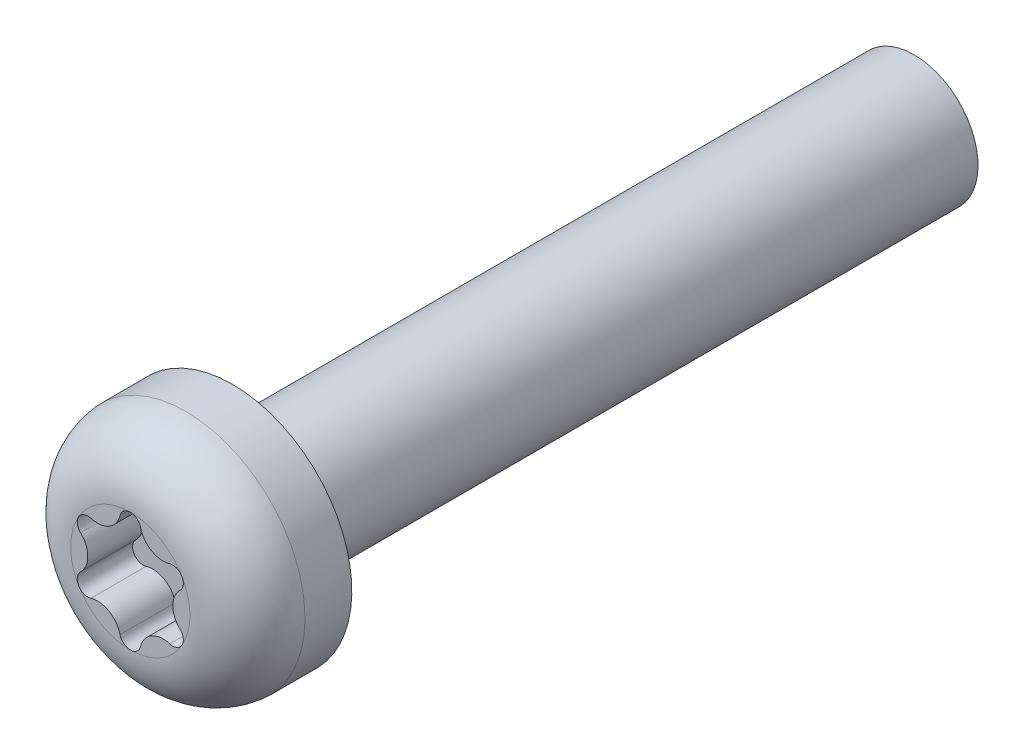
SolidWorks part; units mm, degrees
material "AISI Acier à outil type A2"
ref_plane "Face" through (0, 0, 0) normal (0, 0, 1) x (1, 0, 0)
ref_plane "Dessus" through (0, 0, 0) normal (0, 1, 0) x (1, 0, 0)
ref_plane "Droite" through (0, 0, 0) normal (1, 0, 0) x (0, 0, -1)
sketch "Esquisse1" plane through (0, 0, 0) normal (1, 0, 0) x (0, 0, -1)
  line L0 (-2.4, 0) -> (-2.4, 1.4)
  line L1 (-1.1, 2.8) -> (0, 2.8)
  line L2 (0, 2.8) -> (0, 1.5)
  line L3 (0, 1.5) -> (16, 1.5)
  line L4 (16, 1.5) -> (16, 0)
  line L5 (16, 0) -> (-2.4, 0)
  line L6 (-2.4, 0) -> (-4.3313, 0) construction
  arc A0 (-2.4, 1.4) -> (-1.1, 2.8) centre (-0.9962, 1.4) cw
  dimension "L" = 16
  dimension "K" = 2.4
  dimension "T" = 1.3
  dimension "M" = 3
  dimension "DH" = 5.6
  dimension "A" = 2.8
revolve "Révolution1" add sketch "Esquisse1" angle 360 about L6
sketch "Esquisse2" plane through (0, 0, 2.4) normal (0, 0, 1) x (1, 0, 0)
  line L0 (0, -1.0692) -> (0, 1.0844) construction
  line L1 (0, 0) -> (-0.1844, 0.9269) construction
  line L2 (0, 0) -> (0.1807, 0.9086) construction
  line L3 (0, 0) -> (0.8195, 0.4731) construction
  line L4 (0, 0) -> (0.7063, 0.6194) construction
  line L5 (0, 0) -> (0.3928, 0.6804) construction
  line L7 (0, 1.1524) -> (-0.998, 0.5762) construction
  line L8 (-0.998, 0.5762) -> (-0.998, -0.5762) construction
  line L9 (-0.998, -0.5762) -> (0, -1.1524) construction
  line L10 (0, -1.1524) -> (0.998, -0.5762) construction
  line L11 (0.998, -0.5762) -> (0.998, 0.5762) construction
  line L12 (0.998, 0.5762) -> (0, 1.1524) construction
  circle A0 centre (0, 0) radius 1.4 construction
  circle A1 centre (0, 0) radius 1.4 construction
  arc A2 (-0.2407, 1.2102) -> (0.2407, 1.2102) centre (0, 1.1524) cw
  circle A3 centre (0, 0) radius 0.998 construction
  arc A4 (0.2407, 1.2102) -> (0.9277, 0.8136) centre (0.7724, 1.3379) ccw
  arc A5 (0.9277, 0.8136) -> (1.1684, 0.3966) centre (0.998, 0.5762) cw
  arc A6 (1.1684, 0.3966) -> (1.1684, -0.3966) centre (1.5448, 0) ccw
  arc A7 (1.1684, -0.3966) -> (0.9277, -0.8136) centre (0.998, -0.5762) cw
  arc A8 (0.9277, -0.8136) -> (0.2407, -1.2102) centre (0.7724, -1.3379) ccw
  arc A9 (0.2407, -1.2102) -> (-0.2407, -1.2102) centre (0, -1.1524) cw
  arc A10 (-0.2407, -1.2102) -> (-0.9277, -0.8136) centre (-0.7724, -1.3379) ccw
  arc A11 (-0.9277, -0.8136) -> (-1.1684, -0.3966) centre (-0.998, -0.5762) cw
  arc A12 (-1.1684, -0.3966) -> (-1.1684, 0.3966) centre (-1.5448, 0) ccw
  arc A13 (-1.1684, 0.3966) -> (-0.9277, 0.8136) centre (-0.998, 0.5762) cw
  arc A14 (-0.9277, 0.8136) -> (-0.2407, 1.2102) centre (-0.7724, 1.3379) ccw
  point P22 (0.499, 0.8643)
  dimension "D1" = 22.5
  dimension "D2" = 60
  dimension "D3" = 11.25
  dimension "D4" = 6
extrude "Enlèv. mat.-Extru.1" cut sketch "Esquisse2" against normal blind 1.3
equation "\"D3@Esquisse2\" = \"D1@Esquisse2\"/2"
equation "\"D1@Enlèv. mat.-Extru.1\" = \"T@Esquisse1\""
